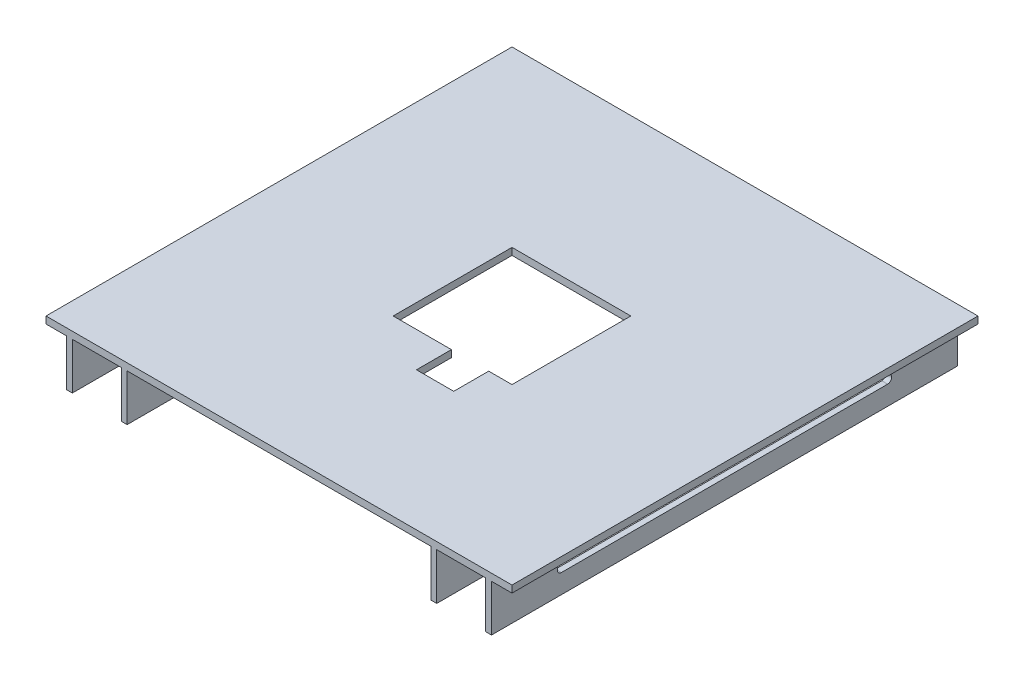
SolidWorks part; units mm, degrees
ref_plane "前视基准面" through (0, 0, 0) normal (0, 0, 1) x (1, 0, 0)
ref_plane "上视基准面" through (0, 0, 0) normal (0, 1, 0) x (1, 0, 0)
ref_plane "右视基准面" through (0, 0, 0) normal (1, 0, 0) x (0, 0, -1)
sketch "草图1" plane through (0, 0, 0) normal (0, 1, 0) x (1, 0, 0)
  line L1 (-100, 100) -> (100, 100)
  line L2 (-100, 100) -> (-100, -100)
  line L3 (-100, -100) -> (100, -100)
  line L4 (100, 100) -> (100, -100)
  line L5 (0, -100) -> (0, 100) construction
  line L6 (-100, 0) -> (100, 0) construction
  point P0 (0, 0)
  dimension "D1" = 200
  dimension "D2" = 200
extrude "凸台-拉伸1" add sketch "草图1" along normal blind 3
sketch "草图2" plane through (0, 0, 0) normal (0, -1, 0) x (1, 0, 0)
  line L0 (0, 0) -> (0, 80.4527) construction
  line L1 (-67.7, 100) -> (-67.7, -100)
  line L2 (-100, 100) -> (100, 100) construction
  line L3 (100, -100) -> (-100, -100) construction
  line L4 (-67.7, -100) -> (-65.2, -100)
  line L5 (-65.2, -100) -> (-65.2, 100)
  line L6 (-65.2, 100) -> (-67.7, 100)
  line L7 (-88.7, 100) -> (-88.7, -100)
  line L8 (-91.2, -100) -> (-91.2, 100)
  line L9 (-91.2, 100) -> (-88.7, 100)
  line L10 (-91.2, -100) -> (-88.7, -100)
  dimension "D1" = 67.7
  dimension "D2" = 2.5
  dimension "D3" = 21
  dimension "D4" = 2.5
extrude "凸台-拉伸2" add sketch "草图2" along normal blind 20
mirror "镜向1" about plane through (0, 0, 0) normal (1, 0, 0) of "凸台-拉伸2"
sketch "草图4" plane through (0, 3, 0) normal (0, 1, 0) x (1, 0, 0)
  line L0 (-78.2, 100) -> (-78.2, -100) construction
  line L5 (15.5, -25.5) -> (15.5, -40.5)
  line L6 (-25.5, 25.5) -> (25.5, 25.5)
  line L7 (-67.7, 100) -> (-88.7, 100) construction
  line L8 (-88.7, -100) -> (-67.7, -100) construction
  line L9 (78.2, 100) -> (78.2, -100) construction
  line L10 (88.7, 100) -> (67.7, 100) construction
  line L11 (67.7, -100) -> (88.7, -100) construction
  line L12 (15.5, -40.5) -> (-0.5, -40.5)
  line L13 (-0.5, -40.5) -> (-0.5, -25.5)
  line L14 (-25.5, 25.5) -> (-25.5, -25.5)
  line L15 (-25.5, -25.5) -> (-0.5, -25.5)
  line L16 (25.5, 25.5) -> (25.5, -25.5)
  line L17 (0, -25) -> (0, 25.5) construction
  line L18 (-25.5, 0) -> (25.5, 0) construction
  line L19 (15.5, -25.5) -> (25.5, -25.5)
  point P0 (0, 0)
  dimension "D3" = 51
  dimension "D4" = 15
  dimension "D5" = 16
  dimension "D1" = 10
  dimension "D2" = 51
sketch "草图5" plane through (91.2, 0, 0) normal (1, 0, 0) x (0, 0, -1)
  line L0 (-100, -10) -> (-70, -10) construction
  line L1 (-100, -20) -> (-100, 0) construction
  line L2 (0, -10) -> (0, 7.9927) construction
  line L3 (-70, -8.25) -> (70, -8.25)
  line L4 (-70, -11.75) -> (70, -11.75)
  arc A0 (-70, -8.25) -> (-70, -11.75) centre (-70, -10) ccw
  arc A1 (70, -8.25) -> (70, -11.75) centre (70, -10) cw
  dimension "D2" = 3.5
  dimension "D1" = 30
extrude "切除-拉伸2" cut sketch "草图5" against normal through all
extrude "切除-拉伸3" cut sketch "草图4" against normal blind 10
sketch "草图6" plane through (0, 0, 100) normal (0, 0, 1) x (1, 0, 0)
  line L20 (-100, 0) -> (-91.2, 0)
  line L21 (-91.2, 0) -> (-91.2, -20)
  line L22 (-91.2, -20) -> (-88.7, -20)
  line L23 (-88.7, -20) -> (-88.7, 0)
  line L24 (-88.7, 0) -> (-67.7, 0)
  line L25 (-67.7, 0) -> (-67.7, -20)
  line L26 (-67.7, -20) -> (-65.2, -20)
  line L27 (-65.2, -20) -> (-65.2, 0)
  line L28 (-65.2, 0) -> (65.2, 0)
  line L29 (65.2, 0) -> (65.2, -20)
  line L30 (65.2, -20) -> (67.7, -20)
  line L31 (67.7, -20) -> (67.7, 0)
  line L32 (67.7, 0) -> (88.7, 0)
  line L33 (88.7, 0) -> (88.7, -20)
  line L34 (88.7, -20) -> (91.2, -20)
  line L35 (91.2, -20) -> (91.2, 0)
  line L36 (91.2, 0) -> (100, 0)
  line L37 (100, 0) -> (100, 3)
  line L38 (100, 3) -> (-100, 3)
  line L39 (-100, 3) -> (-100, 0)
  line L40 (-100, 0) -> (-91.2, 0)
  line L41 (-91.2, 0) -> (-91.2, -20)
  line L42 (-91.2, -20) -> (-88.7, -20)
  line L43 (-88.7, -20) -> (-88.7, 0)
  line L44 (-88.7, 0) -> (-67.7, 0)
  line L45 (-67.7, 0) -> (-67.7, -20)
  line L46 (-67.7, -20) -> (-65.2, -20)
  line L47 (-65.2, -20) -> (-65.2, 0)
  line L48 (-65.2, 0) -> (65.2, 0)
  line L49 (65.2, 0) -> (65.2, -20)
  line L50 (65.2, -20) -> (67.7, -20)
  line L51 (67.7, -20) -> (67.7, 0)
  line L52 (67.7, 0) -> (88.7, 0)
  line L53 (88.7, 0) -> (88.7, -20)
  line L54 (88.7, -20) -> (91.2, -20)
  line L55 (91.2, -20) -> (91.2, 0)
  line L56 (91.2, 0) -> (100, 0)
  line L57 (100, 0) -> (100, 3)
  line L58 (100, 3) -> (-100, 3)
  line L59 (-100, 3) -> (-100, 0)
  dimension "D1" = 0
